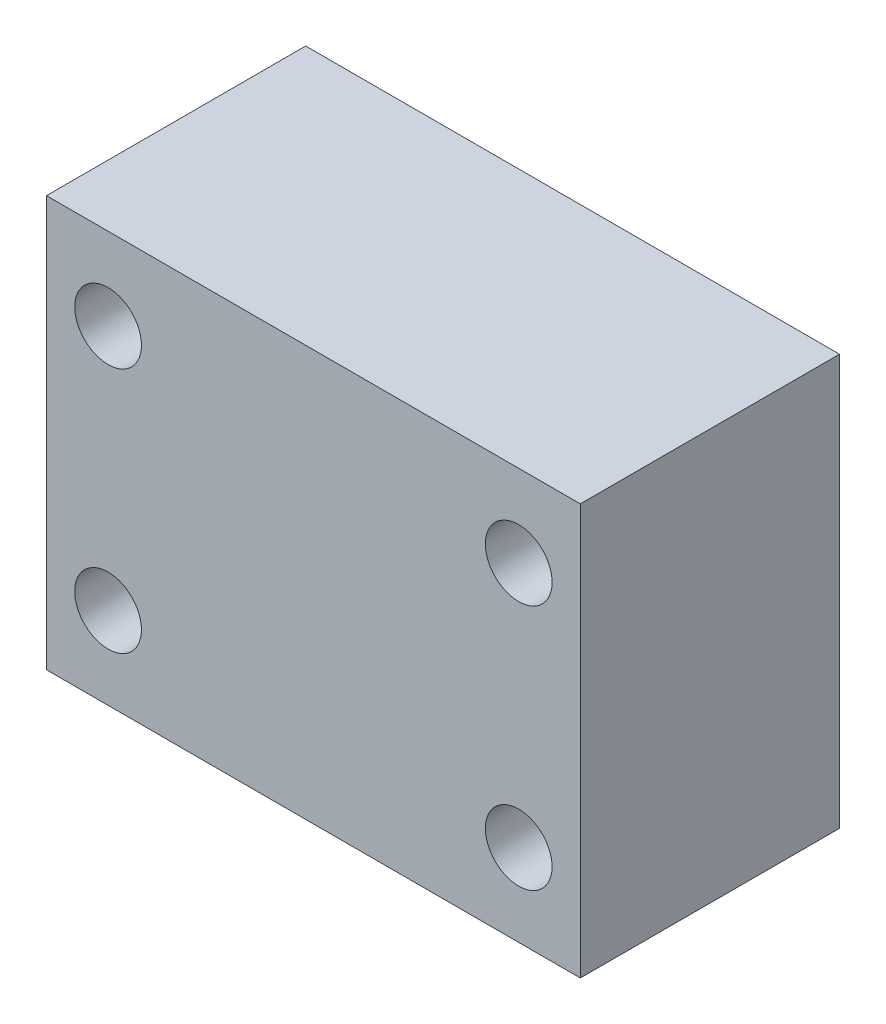
SolidWorks part; units mm, degrees
ref_plane "Front Plane" through (0, 0, 0) normal (0, 0, 1) x (1, 0, 0)
ref_plane "Top Plane" through (0, 0, 0) normal (0, 1, 0) x (1, 0, 0)
ref_plane "Right Plane" through (0, 0, 0) normal (1, 0, 0) x (0, 0, -1)
sketch "Sketch1" plane through (0, 0, 0) normal (0, 0, 1) x (1, 0, 0)
  line L1 (-26, -20) -> (26, -20)
  line L2 (-26, -20) -> (-26, 20)
  line L3 (-26, 20) -> (26, 20)
  line L4 (26, -20) -> (26, 20)
  line L5 (-26, -20) -> (26, 20) construction
  line L6 (-26, 20) -> (26, -20) construction
  point P0 (0, 0)
  dimension "D1" = 40
  dimension "D2" = 52
extrude "Boss-Extrude1" add sketch "Sketch1" along normal mid plane 25.25
sketch "Sketch2" plane through (0, 0, 12.625) normal (0, 0, 1) x (1, 0, 0)
  line L1 (-20, -12) -> (20, -12) construction
  line L2 (-20, -12) -> (-20, 12) construction
  line L3 (-20, 12) -> (20, 12) construction
  line L4 (20, -12) -> (20, 12) construction
  line L5 (-20, -12) -> (20, 12) construction
  line L6 (-20, 12) -> (20, -12) construction
  circle A0 centre (-20, 12) radius 3.25
  circle A1 centre (20, 12) radius 3.25
  circle A2 centre (-20, -12) radius 3.25
  circle A3 centre (20, -12) radius 3.25
  point P0 (0, 0)
  dimension "D3" = 6.5
  dimension "D1" = 40
  dimension "D2" = 24
extrude "Cut-Extrude1" cut sketch "Sketch2" against normal through all
